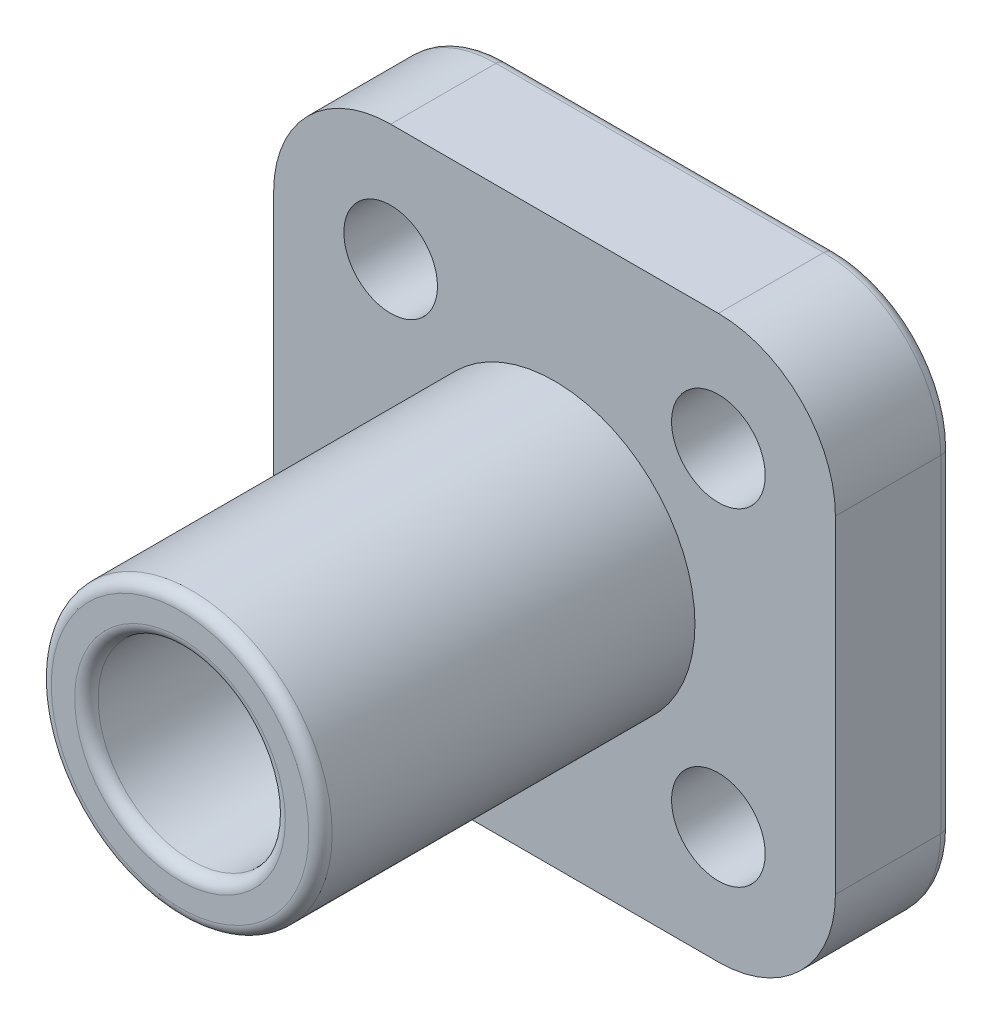
SolidWorks part; units mm, degrees
ref_plane "Plan de face" through (0, 0, 0) normal (0, 0, 1) x (1, 0, 0)
ref_plane "Plan de dessus" through (0, 0, 0) normal (0, 1, 0) x (1, 0, 0)
ref_plane "Plan de droite" through (0, 0, 0) normal (1, 0, 0) x (0, 0, -1)
sketch "Esquisse1" plane through (0, 0, 0) normal (0, 0, 1) x (1, 0, 0)
  line L0 (-7, 7) -> (7, 7) construction
  line L1 (7, -12) -> (-7, -12)
  line L2 (12, -7) -> (12, 7)
  line L3 (7, 12) -> (-7, 12)
  line L4 (-12, -7) -> (-12, 7)
  line L5 (12, -12) -> (-12, 12) construction
  line L6 (12, 12) -> (-12, -12) construction
  line L7 (-7, 7) -> (-7, -7) construction
  arc A0 (7, -12) -> (12, -7) centre (7, -7) ccw
  arc A1 (-7, -12) -> (-12, -7) centre (-7, -7) cw
  arc A2 (12, 7) -> (7, 12) centre (7, 7) ccw
  arc A3 (-7, 12) -> (-12, 7) centre (-7, 7) ccw
  circle A4 centre (-7, 7) radius 2
  circle A5 centre (7, 7) radius 2
  circle A6 centre (7, -7) radius 2
  circle A7 centre (-7, -7) radius 2
  point P0 (0, 0)
  dimension "D2" = 5
  dimension "D3" = 4
  dimension "D1" = 14
  dimension "D6" = 14
  dimension "D7" = 14
  dimension "D4" = 2
  dimension "D5" = 2
extrude "Boss.-Extru.1" add sketch "Esquisse1" along normal blind 5
sketch "Esquisse2" plane through (0, 0, 5) normal (0, 0, 1) x (1, 0, 0)
  circle A0 centre (0, 0) radius 6
  circle A1 centre (0, 0) radius 4
  dimension "D1" = 8
  dimension "D2" = 12
extrude "Boss.-Extru.2" add sketch "Esquisse2" along normal blind 16 contours A0 | A1
sketch "Esquisse3" plane through (0, 0, 5) normal (0, 0, 1) x (1, 0, 0)
  circle A0 centre (0, 0) radius 4
extrude "Enlèv. mat.-Extru.1" cut sketch "Esquisse3" against normal up to next
fillet "Congé1" radius 0.5 15 edges at (6, 0, 21) (4, 0, 21) (-5, -7, 0) (9, -7, 0) (9, 7, 0) (-5, 7, 0) (12, 0, 0) (10.5355, 10.5355, 0) (0, 12, 0) (-10.5355, 10.5355, 0) (-12, 0, 0) (-10.5355, -10.5355, 0) (0, -12, 0) (10.5355, -10.5355, 0) (4, 0, 0)
